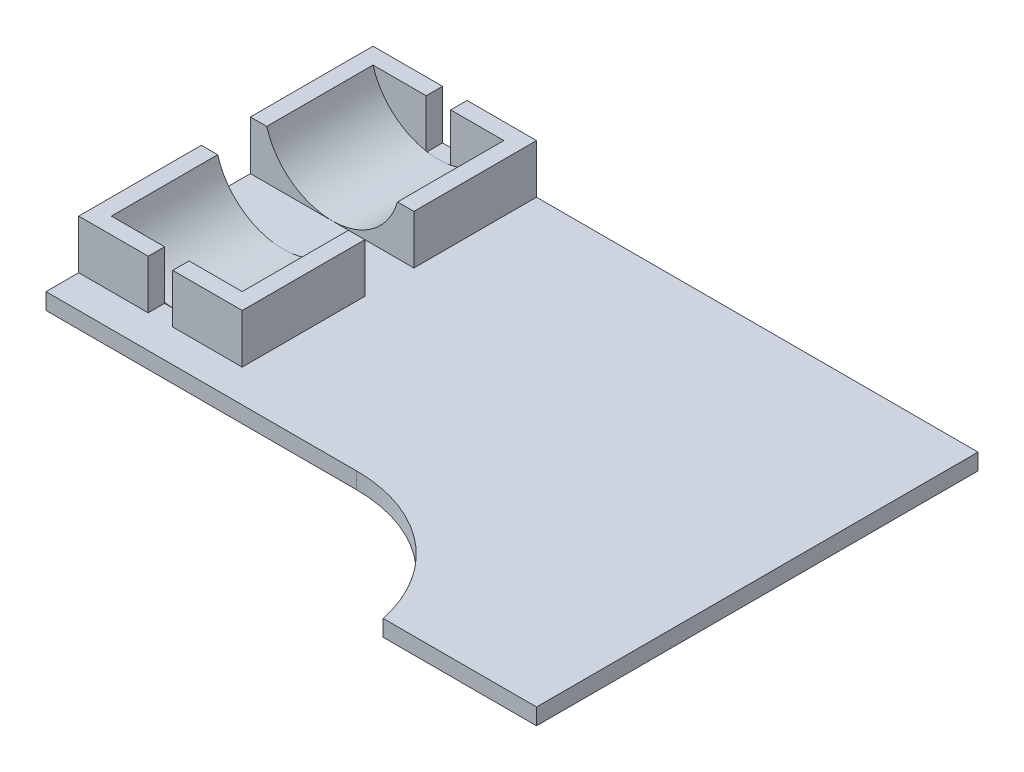
SolidWorks part; units mm, degrees
ref_plane "Front Plane" through (0, 0, 0) normal (0, 0, 1) x (1, 0, 0)
ref_plane "Top Plane" through (0, 0, 0) normal (0, 1, 0) x (1, 0, 0)
ref_plane "Right Plane" through (0, 0, 0) normal (1, 0, 0) x (0, 0, -1)
sketch "Sketch1" plane through (0, 0, 0) normal (0, 1, 0) x (1, 0, 0)
  line L0 (-185, -65) -> (5, -65)
  line L1 (-185, 135) -> (185, 135)
  line L2 (-185, 135) -> (-185, -65)
  line L4 (185, 135) -> (185, -135)
  line L8 (91.1823, -135) -> (185, -135)
  arc A0 (5, -65) -> (91.1823, -135) centre (5, -153.0528) cw
  point P0 (0, 0)
  point P1 (0, 0)
  point P3 (185, -98.2977)
  point P8 (91.1823, -135)
extrude "Boss-Extrude1" add sketch "Sketch1" along normal blind 10
sketch "Sketch2" plane through (0, 10, 0) normal (0, 1, 0) x (1, 0, 0)
  line L0 (-175, -35) -> (-175, 30)
  line L1 (-175, -35) -> (-142.5, -35)
  line L2 (-175, 125) -> (-142.5, 125)
  line L3 (-95, -35) -> (-95, 30)
  line L12 (-185, 135) -> (-185, -65) construction
  line L13 (-185, 135) -> (-142.5, 135)
  line L14 (-85, -45) -> (-85, 30)
  line L15 (-185, -45) -> (-142.5, -45)
  line L16 (-185, -45) -> (-185, 30)
  line L17 (-135, 196.4351) -> (-135, -108.7974) construction
  line L18 (-142.5, 135) -> (-142.5, 125)
  line L19 (-127.5, 135) -> (-127.5, 125)
  line L20 (-127.5, 135) -> (-85, 135)
  line L21 (-185, 135) -> (-85, 135) construction
  line L22 (-127.5, 125) -> (-95, 125)
  line L23 (-175, 125) -> (-95, 125) construction
  line L24 (-208.7616, 45) -> (-62.2564, 45) construction
  line L25 (-127.5, -45) -> (-127.5, -35)
  line L26 (-142.5, -45) -> (-142.5, -35)
  line L27 (-127.5, -35) -> (-95, -35)
  line L28 (-175, -35) -> (-95, -35) construction
  line L29 (-127.5, -45) -> (-85, -45)
  line L30 (-185, -45) -> (-85, -45) construction
  line L31 (185, 135) -> (-185, 135) construction
  line L32 (-175, 60) -> (-185, 60)
  line L33 (-175, 30) -> (-185, 30)
  line L34 (-95, 60) -> (-85, 60)
  line L35 (-95, 30) -> (-85, 30)
  line L36 (-175, 60) -> (-175, 125)
  line L37 (-175, -35) -> (-175, 125) construction
  line L38 (-185, 60) -> (-185, 135)
  line L39 (-185, -45) -> (-185, 135) construction
  line L40 (-85, 60) -> (-85, 135)
  line L41 (-85, -45) -> (-85, 135) construction
  line L42 (-95, 60) -> (-95, 125)
  line L43 (-95, -35) -> (-95, 125) construction
  point P14 (-135, 135.0621)
  point P18 (-175, 45)
  dimension "D1" = 160
  dimension "D2" = 80
  dimension "D3" = 10
  dimension "D4" = 7.5
  dimension "D5" = 50
  dimension "D6" = 30
  dimension "D7" = 15
extrude "Boss-Extrude2" add sketch "Sketch2" along normal blind 30
sketch "Sketch3" plane through (0, 0, -125) normal (0, 0, 1) x (1, 0, 0)
  line L0 (-127.5, 10) -> (-142.5, 10) construction
  line L1 (-175, 40) -> (-142.5, 40) construction
  line L2 (-142.5, 40) -> (-185, 40) construction
  line L3 (-127.5, 40) -> (-95, 40) construction
  line L4 (-142.5, 10) -> (-127.5, 10)
  line L8 (-175, 10) -> (-142.5, 10)
  line L9 (-142.5, 10) -> (-142.5, 40)
  line L10 (-142.5, 40) -> (-175, 40)
  line L11 (-175, 40) -> (-175, 10)
  line L12 (-175, 10) -> (-142.5, 10)
  line L13 (-142.5, 10.6806) -> (-142.5, 40)
  line L14 (-142.5, 40) -> (-175, 40)
  line L15 (-175, 40) -> (-175, 10)
  line L16 (-127.5, 10) -> (-95, 10)
  line L17 (-95, 10) -> (-95, 40)
  line L18 (-95, 40) -> (-127.5, 40)
  line L19 (-127.5, 40) -> (-127.5, 10)
  line L20 (-127.5, 10) -> (-95, 10)
  line L21 (-95, 10) -> (-95, 40)
  line L22 (-95, 40) -> (-127.5, 40)
  line L23 (-127.5, 40) -> (-127.5, 10.6806)
  arc A0 (-175, 40) -> (-95, 40) centre (-135, 51.6667) ccw
  point P0 (-135, 10)
  line M9 (-175, 10) -> (-142.5, 10)
  line M10 (-142.5, 10) -> (-142.5, 40)
  line M12 (-175, 40) -> (-175, 10)
  dimension "D1" = 0
  dimension "D2" = 0
extrude "Boss-Extrude3" add sketch "Sketch3" along normal up to surface (160 mm away) contours A0 M12 M9 M10 | A0 L4 L20 L21 | A0 L4 M10
sketch "Sketch5" plane through (-185, 0, 0) normal (-1, 0, 0) x (0, 0, 1)
  line L0 (-60, 40) -> (-30, 40)
  line L10 (-135, 0) -> (65, 0)
  line L11 (65, 0) -> (65, 10)
  line L12 (65, 10) -> (45, 10)
  line L13 (45, 10) -> (45, 40)
  line L14 (45, 40) -> (-30, 40)
  line L15 (-30, 40) -> (-30, 10)
  line L16 (-30, 10) -> (-60, 10)
  line L17 (-60, 10) -> (-60, 40)
  line L18 (-60, 40) -> (-135, 40)
  line L19 (-135, 40) -> (-135, 0)
  line L25 (-30, 40) -> (-30, 10)
  line L26 (-30, 10) -> (-60, 10)
  line L27 (-60, 10) -> (-60, 40)
  dimension "D1" = 0
extrude "Cut-Extrude1" cut sketch "Sketch5" against normal through all both and the other way through all
